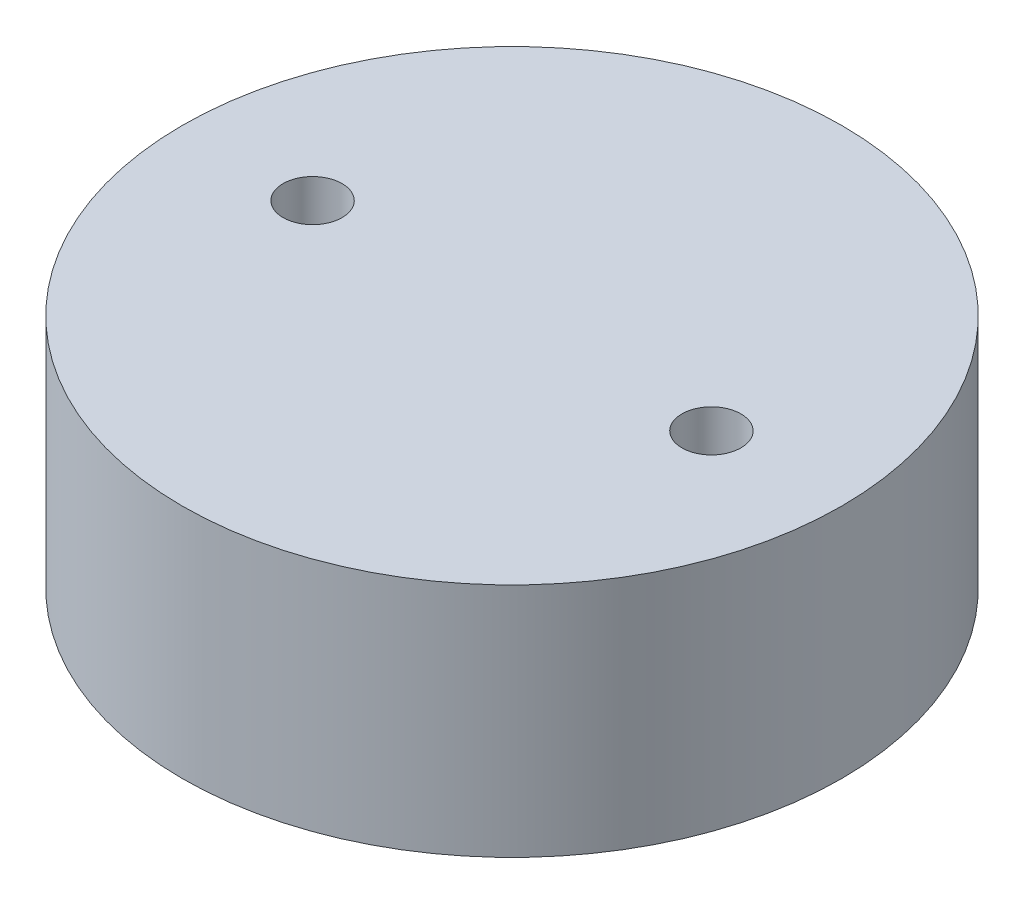
SolidWorks part; units mm, degrees
ref_plane "Front Plane" through (0, 0, 0) normal (0, 0, 1) x (1, 0, 0)
ref_plane "Top Plane" through (0, 0, 0) normal (0, 1, 0) x (1, 0, 0)
ref_plane "Right Plane" through (0, 0, 0) normal (1, 0, 0) x (0, 0, -1)
sketch "Sketch1" plane through (0, 0, 0) normal (0, 1, 0) x (1, 0, 0)
  line L0 (0, 13.97) -> (0, -13.97) construction
  line L1 (-13.97, 0) -> (13.97, 0) construction
  circle A0 centre (0, 0) radius 13.97
  circle A1 centre (-8.45, 0) radius 1.25
  circle A2 centre (8.45, 0) radius 1.25
  dimension "D2" = 2.5
  dimension "D3" = 27.94
  dimension "D1" = 8.45
extrude "Boss-Extrude1" add sketch "Sketch1" along normal blind 10
equation "\"D1@Sketch1\"=1.69/2"
